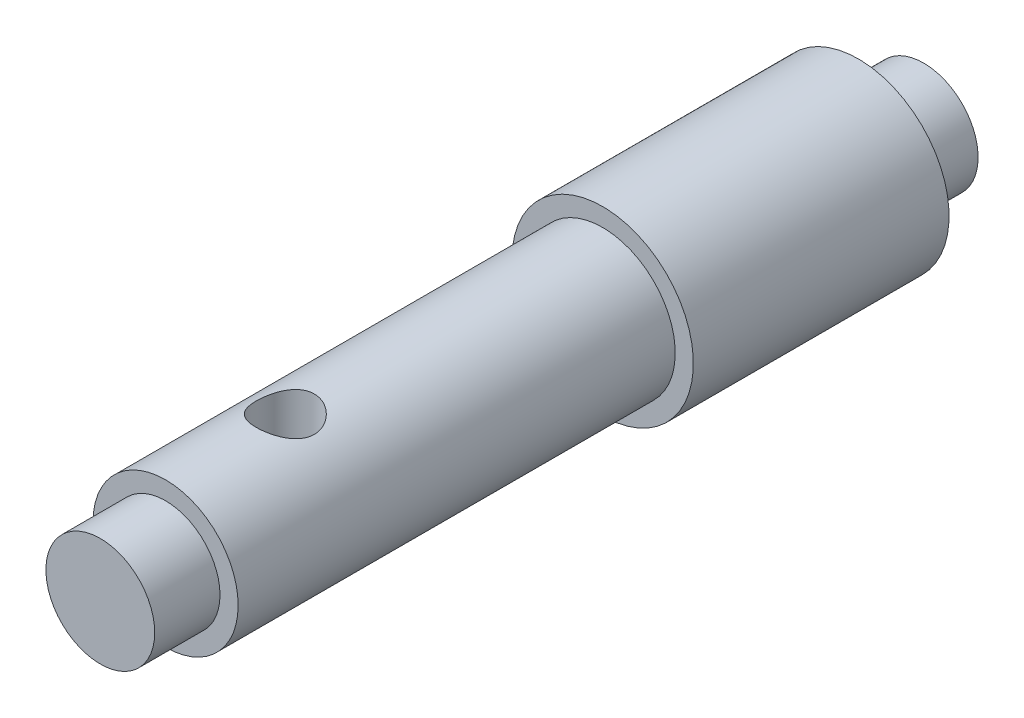
SolidWorks part; units mm, degrees
material "1060 合金"
ref_plane "正面" through (0, 0, 0) normal (0, 0, 1) x (1, 0, 0)
ref_plane "平面" through (0, 0, 0) normal (0, 1, 0) x (1, 0, 0)
ref_plane "右側面" through (0, 0, 0) normal (1, 0, 0) x (0, 0, -1)
sketch "ｽｹｯﾁ1" plane through (0, 0, 0) normal (0, 0, 1) x (1, 0, 0)
  circle A1 centre (0, 0) radius 4
  dimension "D1" = 8
extrude "ﾎﾞｽ - 押し出し1" add sketch "ｽｹｯﾁ1" along normal blind 45.4
sketch "ｽｹｯﾁ2" plane through (0, 0, 0) normal (0, 0, -1) x (-1, 0, 0)
  circle A0 centre (0, 0) radius 3
  circle A1 centre (0, 0) radius 4
  dimension "D1" = 8
  dimension "D2" = 6
extrude "ｶｯﾄ - 押し出し1" cut sketch "ｽｹｯﾁ2" against normal blind 3.6
sketch "ｽｹｯﾁ3" plane through (0, 0, 45.4) normal (0, 0, 1) x (1, 0, 0)
  circle A0 centre (0, 0) radius 3
  circle A1 centre (0, 0) radius 4
  dimension "D1" = 8
  dimension "D2" = 6
extrude "ｶｯﾄ - 押し出し2" cut sketch "ｽｹｯﾁ3" against normal blind 3.6
sketch "ｽｹｯﾁ4" plane through (0, 0, 0) normal (0, 1, 0) x (1, 0, 0)
  line L0 (0, 0) -> (0, -45.4) construction
  line L1 (-3, -45.4) -> (3, -45.4) construction
  circle A0 centre (0, -35.2) radius 1.6
  dimension "D1" = 3.2
  dimension "D2" = 10.2
extrude "ｶｯﾄ - 押し出し3" cut sketch "ｽｹｯﾁ4" against normal through all both and the other way through all
sketch "ｽｹｯﾁ5" plane through (0, 0, 3.6) normal (0, 0, -1) x (-1, 0, 0)
  circle A0 centre (0, 0) radius 4
  circle A1 centre (0, 0) radius 5
  dimension "D1" = 10
  dimension "D2" = 8
extrude "ﾎﾞｽ - 押し出し2" add sketch "ｽｹｯﾁ5" against normal blind 14.1
